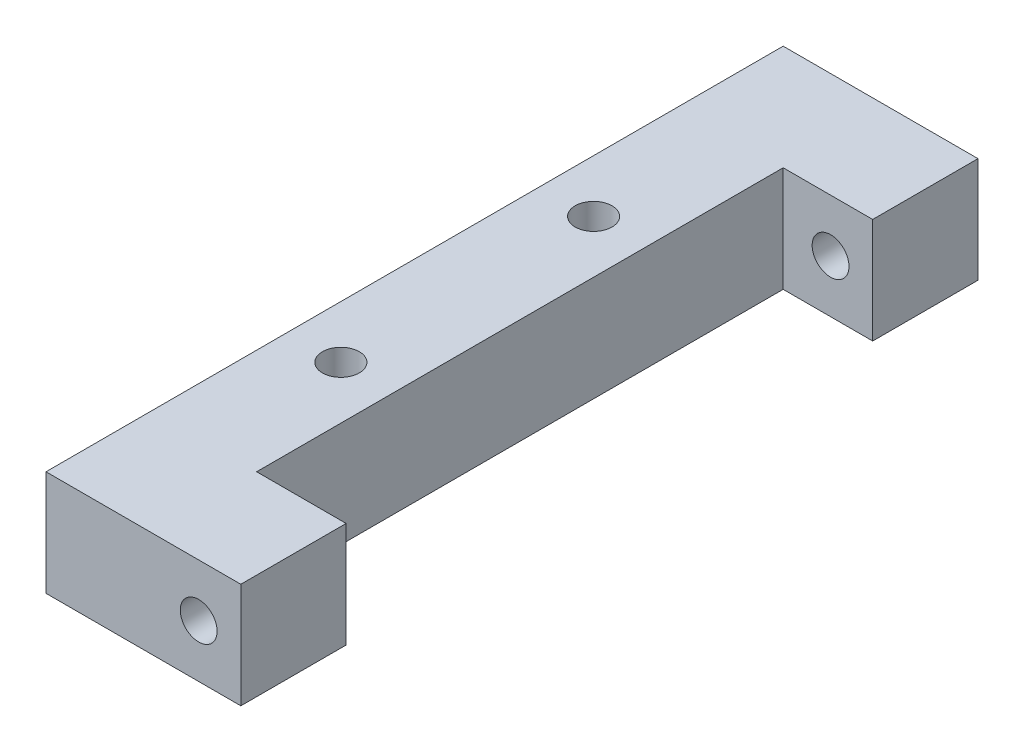
SolidWorks part; units mm, degrees
ref_plane "Front Plane" through (0, 0, 0) normal (0, 0, 1) x (1, 0, 0)
ref_plane "Top Plane" through (0, 0, 0) normal (0, 1, 0) x (1, 0, 0)
ref_plane "Right Plane" through (0, 0, 0) normal (1, 0, 0) x (0, 0, -1)
sketch "Sketch1" plane through (0, 0, 0) normal (0, 0, 1) x (1, 0, 0)
  line L1 (-9.25, 5) -> (9.25, 5)
  line L2 (-9.25, 5) -> (-9.25, -5)
  line L3 (-9.25, -5) -> (9.25, -5)
  line L4 (9.25, 5) -> (9.25, -5)
  line L5 (-9.25, 5) -> (9.25, -5) construction
  line L6 (-9.25, -5) -> (9.25, 5) construction
  point P0 (0, 0)
  dimension "D1" = 10
  dimension "D2" = 18.5
extrude "Boss-Extrude1" add sketch "Sketch1" along normal blind 10
sketch "Sketch2" plane through (0, 0, 10) normal (0, 0, 1) x (1, 0, 0)
  line L1 (-9.25, -5) -> (9.25, -5) construction
  line L2 (-9.25, 5) -> (0.75, 5)
  line L3 (-9.25, 5) -> (-9.25, -5)
  line L4 (-9.25, -5) -> (0.75, -5)
  line L5 (0.75, 5) -> (0.75, -5)
  dimension "D1" = 10
extrude "Boss-Extrude2" add sketch "Sketch2" along normal blind 50
sketch "Sketch3" plane through (0, 0, 60) normal (0, 0, 1) x (1, 0, 0)
  line L1 (-9.25, 5) -> (9.25, 5)
  line L2 (-9.25, 5) -> (-9.25, -5)
  line L3 (-9.25, -5) -> (9.25, -5)
  line L4 (9.25, 5) -> (9.25, -5)
extrude "Boss-Extrude3" add sketch "Sketch3" along normal blind 10
sketch "Sketch4" plane through (0, 0, 70) normal (0, 0, 1) x (1, 0, 0)
  line L0 (9.25, -5) -> (9.25, 5) construction
  circle A0 centre (5.25, 0) radius 1.75
  dimension "D1" = 3.5
  dimension "D2" = 4
extrude "Cut-Extrude1" cut sketch "Sketch4" against normal through all
sketch "Sketch5" plane through (0, 5, 0) normal (0, 1, 0) x (1, 0, 0)
  line L1 (-9.25, -70) -> (-9.25, 0) construction
  line L2 (-9.25, -70) -> (-9.25, 0) construction
  circle A0 centre (-4.25, -23) radius 1.75
  circle A1 centre (-4.25, -47) radius 1.75
  point P9 (-9.25, -35)
  dimension "D1" = 3.5
  dimension "D3" = 3.5
  dimension "D2" = 5
  dimension "D4" = 24
  dimension "D5" = 12
extrude "Cut-Extrude2" cut sketch "Sketch5" against normal through all
